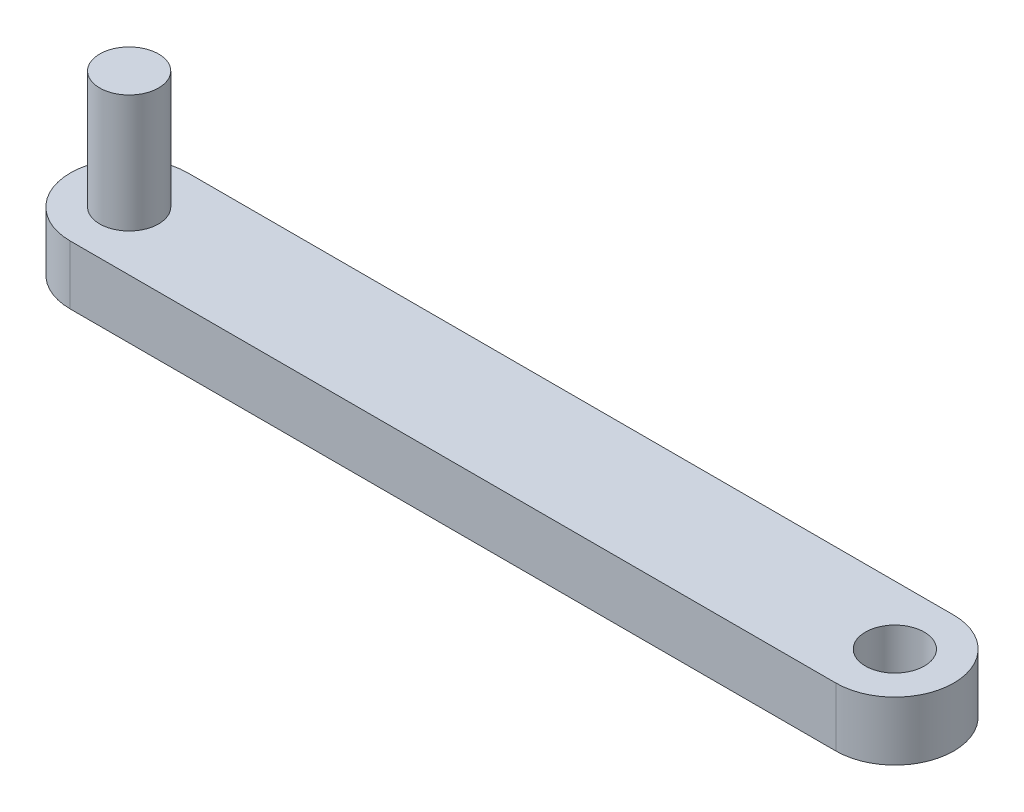
SolidWorks part; units mm, degrees
ref_plane "Front Plane" through (0, 0, 0) normal (0, 0, 1) x (1, 0, 0)
ref_plane "Top Plane" through (0, 0, 0) normal (0, 1, 0) x (1, 0, 0)
ref_plane "Right Plane" through (0, 0, 0) normal (1, 0, 0) x (0, 0, -1)
sketch "Sketch1" plane through (0, 0, 0) normal (0, 1, 0) x (1, 0, 0)
  line L1 (-65, -10) -> (65, -10)
  line L3 (-65, 10) -> (65, 10)
  line L5 (-65, -10) -> (65, 10) construction
  line L6 (-65, 10) -> (65, -10) construction
  arc A0 (-65, -10) -> (-65, 10) centre (-65, 0) cw
  arc A1 (65, -10) -> (65, 10) centre (65, 0) ccw
  circle A2 centre (-65, 0) radius 5
  circle A3 centre (65, 0) radius 5
  point P0 (0, 0)
  dimension "D3" = 10
  dimension "D4" = 10
  dimension "D1" = 20
  dimension "D2" = 130
extrude "Boss-Extrude1" add sketch "Sketch1" along normal mid plane 10
sketch "Sketch2" plane through (0, 0, 0) normal (0, 1, 0) x (1, 0, 0)
  circle A0 centre (-65, 0) radius 5
  dimension "D1" = 10
extrude "Boss-Extrude2" add sketch "Sketch2" along normal blind 25 and the other way blind 5
